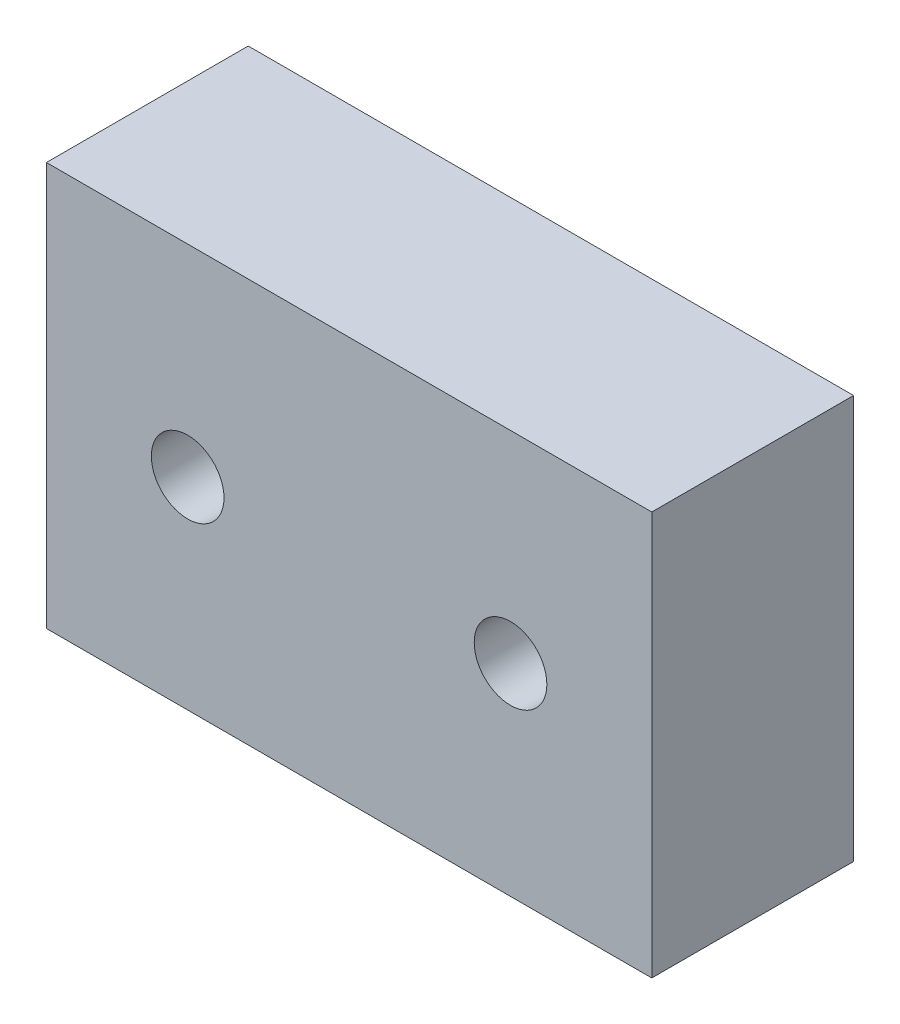
SolidWorks part; units mm, degrees
ref_plane "Plan de face" through (0, 0, 0) normal (0, 0, 1) x (1, 0, 0)
ref_plane "Plan de dessus" through (0, 0, 0) normal (0, 1, 0) x (1, 0, 0)
ref_plane "Plan de droite" through (0, 0, 0) normal (1, 0, 0) x (0, 0, -1)
sketch "Esquisse1" plane through (0, 0, 0) normal (0, 0, 1) x (1, 0, 0)
  line L0 (-25.422, -33.6083) -> (-10.422, -33.6083)
  line L1 (-10.422, -33.6083) -> (-10.422, -23.6083)
  line L2 (-10.422, -23.6083) -> (-25.422, -23.6083)
  line L3 (-25.422, -23.6083) -> (-25.422, -33.6083)
  dimension "D1" = 15
  dimension "D2" = 10
  dimension "D3" = 15
  dimension "D4" = 10
extrude "Boss.-Extru.1" add sketch "Esquisse1" along normal blind 3 and the other way blind 2
sketch "Esquisse2" plane through (0, 0, -2) normal (0, 0, -1) x (-1, 0, 0)
  line L0 (10.422, -23.6083) -> (10.422, -33.6083) construction
  line L1 (10.422, -33.6083) -> (25.422, -33.6083) construction
  line L3 (25.422, -23.6083) -> (25.422, -33.6083) construction
  line L5 (25.422, -28.6083) -> (21.922, -28.6083) construction
  line L7 (21.922, -28.6083) -> (13.922, -28.6083) construction
  line L8 (13.922, -28.6083) -> (10.422, -28.6083) construction
  dimension "D1" = 15
  dimension "D2" = 3.5
  dimension "D3" = 8
  dimension "D4" = 3.5
hole_wizard "Dégagement M1.61" positions "Esquisse3D2" profile "Esquisse8" hole size "M1.6" standard "Ansi Metric"
sketch3d "Esquisse3D2"
  point P0 (-21.922, -28.6083, -2)
  point P3 (-13.922, -28.6083, -2)
sketch "Esquisse8" plane through (-21.922, -28.6083, -2) normal (1, 0, 0) x (0, 1, 0)
  line L0 (0, 0) -> (0, 28.7108)
  line L1 (0, 28.7108) -> (0.9, 28.17)
  line L2 (0.9, 28.17) -> (0.9, 0)
  line L5 (0.9, 0) -> (0, 0)
  line L10 (0, 28.7108) -> (-0.9, 28.17) construction
  line L11 (0, -6.35) -> (0, 107.95) construction
  dimension "Diamètre du perçage" = 1.8
  dimension "Profondeur du perçage" = 28.17
  dimension "Angle de pointe" = 118
sketch "Esquisse9" plane through (0, -33.6083, 0) normal (0, -1, 0) x (1, 0, 0)
  line L0 (-25.422, 3) -> (-25.422, -2) construction
  line L1 (-25.422, -2) -> (-25.422, 0.5) construction
  line L2 (-25.422, 0.5) -> (-17.922, 0.5) construction
  dimension "D1" = 7.5
hole_wizard "Dégagement M1.62" positions "Esquisse3D3" profile "Esquisse10" hole size "M1.6" standard "Ansi Metric"
sketch3d "Esquisse3D3"
  point P0 (-17.922, -33.6083, 0.5)
sketch "Esquisse10" plane through (-17.922, -33.6083, 0.5) normal (1, 0, 0) x (0, 0, -1)
  line L0 (0, 0) -> (0, 3.9013)
  line L1 (0, 3.9013) -> (1.5, 3)
  line L2 (1.5, 3) -> (1.5, 0)
  line L5 (1.5, 0) -> (0, 0)
  line L10 (0, 3.9013) -> (-1.5, 3) construction
  line L11 (0, -6.35) -> (0, 107.95) construction
  dimension "Diamètre du perçage" = 3
  dimension "Profondeur du perçage" = 3
  dimension "Angle de pointe" = 118
